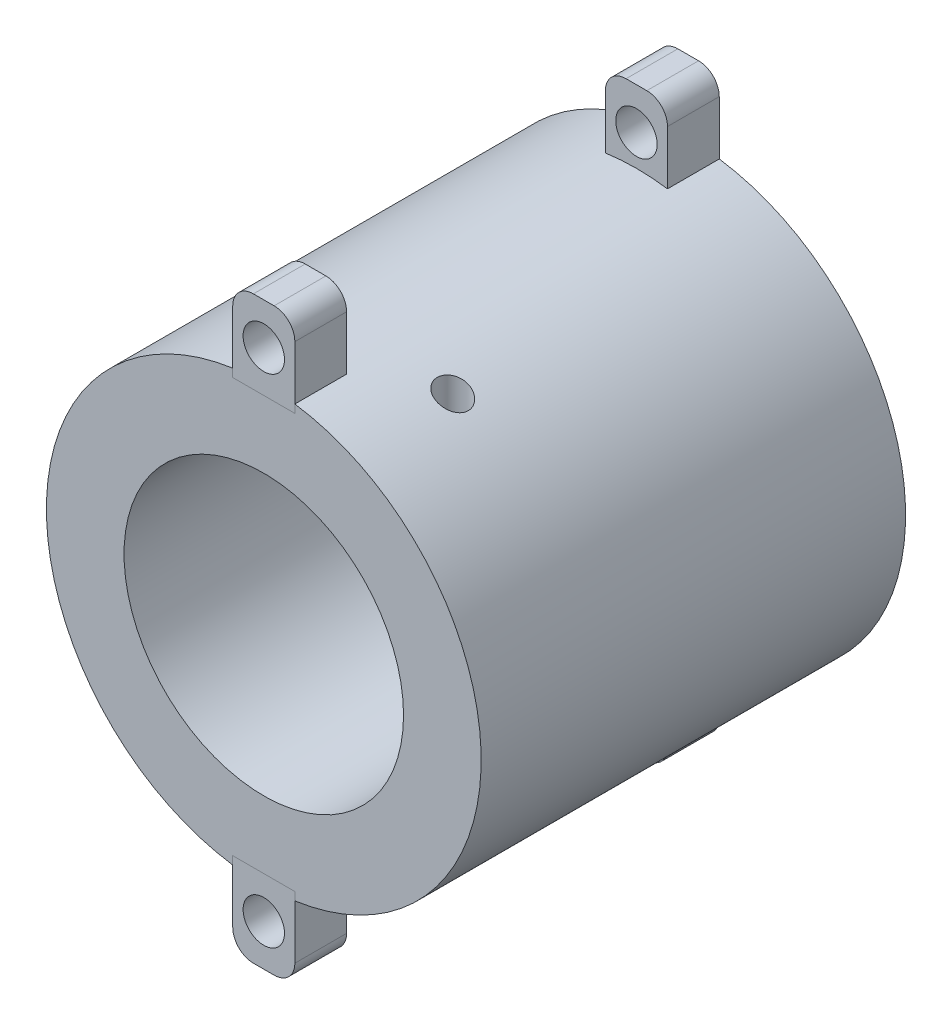
SolidWorks part; units mm, degrees
ref_plane "Front Plane" through (0, 0, 0) normal (0, 0, 1) x (1, 0, 0)
ref_plane "Top Plane" through (0, 0, 0) normal (0, 1, 0) x (1, 0, 0)
ref_plane "Right Plane" through (0, 0, 0) normal (1, 0, 0) x (0, 0, -1)
sketch "Sketch1" plane through (0, 0, 0) normal (0, 0, 1) x (1, 0, 0)
  circle A0 centre (0, 0) radius 13.5
  circle A1 centre (0, 0) radius 19.01
extrude "Boss-Extrude1" add sketch "Sketch1" along normal blind 18
sketch "Sketch2" plane through (0, 0, 18) normal (0, 0, 1) x (1, 0, 0)
  circle A0 centre (0, 0) radius 21
  circle A1 centre (0, 0) radius 13.5
extrude "Boss-Extrude2" add sketch "Sketch2" along normal blind 23 and the other way blind 18
sketch "Sketch3" plane through (0, 0, 0) normal (0, 0, -1) x (-1, 0, 0)
  line L0 (12.8914, 5.46) -> (17.4939, 7.4137)
  line L1 (15.5403, 12.0162) -> (10.9378, 10.0625)
  line L2 (15.5403, 12.0162) -> (19.4476, 2.8111)
  line L3 (19.4476, 2.8111) -> (14.8451, 0.8575)
  line L4 (10.9378, 10.0625) -> (14.8451, 0.8575)
  point P2 (12.8914, 5.46)
  point P6 (17.4939, 7.4137)
  dimension "D1" = 14
  dimension "D2" = 5.46
extrude "Cut-Extrude1" cut sketch "Sketch3" against normal blind 13 contours L1 L4 L3 L2
mirror "Mirror1" about plane through (0, 0, 0) normal (0, 1, 0) of "Cut-Extrude1"
mirror "Mirror2" about plane through (0, 0, 0) normal (1, 0, 0) of "Mirror1", "Cut-Extrude1"
sketch "Sketch4" plane through (0, 0, 0) normal (0, 0, -1) x (-1, 0, 0)
  line L1 (-3, 28) -> (3, 28)
  line L2 (-3, 28) -> (-3, 20)
  line L3 (-3, 20) -> (3, 20)
  line L4 (3, 28) -> (3, 20)
  circle A0 centre (0, 24) radius 2
  point P4 (0, 20)
  dimension "D1" = 4
  dimension "D2" = 20
extrude "Boss-Extrude3" add sketch "Sketch4" along normal blind 0.0001 and the other way blind 5
fillet "Fillet1" radius 2 2 edges at (3, 28, 2.5) (-3, 28, 2.5)
mirror "Mirror5" about plane through (0, 0, 0) normal (0, 1, 0) of "Fillet1", "Boss-Extrude3"
sketch "Sketch7" plane through (0, 0, 41) normal (0, 0, 1) x (1, 0, 0)
  line L1 (-3, 28) -> (3, 28)
  line L2 (-3, 28) -> (-3, 20)
  line L3 (-3, 20) -> (3, 20)
  line L4 (3, 28) -> (3, 20)
  circle A0 centre (0, 24) radius 2
  point P4 (0, 20)
  dimension "D1" = 20
  dimension "D2" = 4
extrude "Boss-Extrude6" add sketch "Sketch7" along normal blind 0.0001 and the other way blind 5
mirror "Mirror6" about plane through (0, 0, 0) normal (0, 1, 0) of "Boss-Extrude6"
fillet "Fillet2" radius 2 4 edges at (-3, 28, 38.5) (3, 28, 38.5) (3, -28, 38.5) (-3, -28, 38.5)
sketch "Sketch9" plane through (0, 0, 0) normal (0, 1, 0) x (1, 0, 0)
  line L0 (0, -22.5501) -> (0, 22.5501) construction
  line L1 (-21, -41) -> (-3, -41) construction
  circle A0 centre (-8.25, -31) radius 1.5
  point P2 (0, 0)
  point P5 (0, 0)
  point P6 (0, 0)
  dimension "D1" = 8.25
  dimension "D2" = 10
extrude "Cut-Extrude2" cut sketch "Sketch9" against normal blind 0.0001 and the other way blind 20
mirror "Mirror7" about plane through (0, 0, 0) normal (1, 0, 0) of "Cut-Extrude2"
